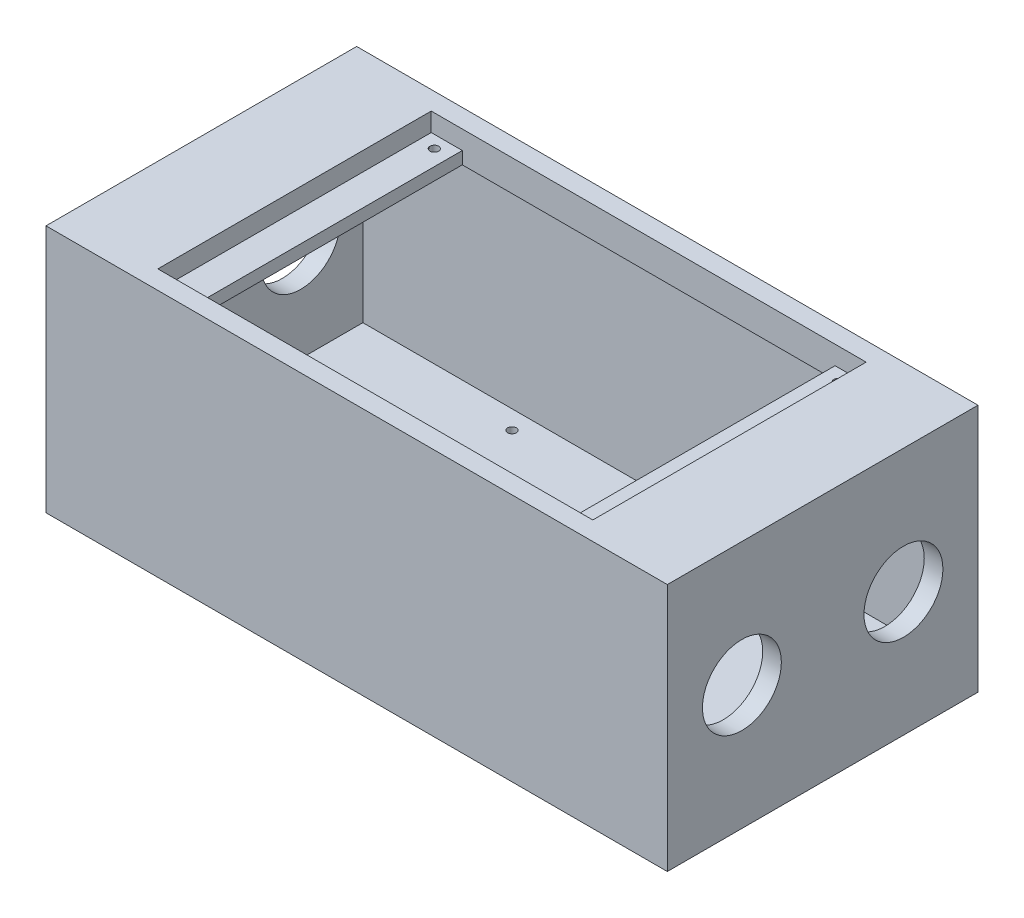
SolidWorks part; units mm, degrees
other "Markup1"
sketch "Sketch8" plane through (250, -50, -125) normal (1, 0, 0) x (0, 0, -1)
ref_plane "Front Plane" through (0, 0, 0) normal (0, 0, 1) x (1, 0, 0)
ref_plane "Top Plane" through (0, 0, 0) normal (0, 1, 0) x (1, 0, 0)
ref_plane "Right Plane" through (0, 0, 0) normal (1, 0, 0) x (0, 0, -1)
sketch "Sketch1" plane through (0, 0, 0) normal (1, 0, 0) x (0, 0, -1)
  line L1 (-125, -100) -> (125, -100)
  line L2 (-125, -100) -> (-125, 100)
  line L3 (-125, 100) -> (125, 100)
  line L4 (125, -100) -> (125, 100)
  line L5 (-125, -100) -> (125, 100) construction
  line L6 (-125, 100) -> (125, -100) construction
  point P0 (0, 0)
  dimension "D1" = 250
  dimension "D2" = 200
extrude "Boss-Extrude1" add sketch "Sketch1" along normal mid plane 500
sketch "Sketch7" plane through (0, 0, 0) normal (0, 1, 0) x (1, 0, 0)
  line L1 (-235, -115) -> (235, -115)
  line L2 (-235, -115) -> (-235, 115)
  line L3 (-235, 115) -> (235, 115)
  line L4 (235, -115) -> (235, 115)
  line L5 (-235, -115) -> (235, 115) construction
  line L6 (-235, 115) -> (235, -115) construction
  point P0 (0, 0)
  dimension "D1" = 470
  dimension "D2" = 230
extrude "Cut-Extrude4" cut sketch "Sketch7" against normal mid plane 160
sketch "Sketch5" plane through (250, 0, 0) normal (1, 0, 0) x (0, 0, -1)
  line L0 (-125, 100) -> (-125, -100) construction
  circle A0 centre (-65, 0) radius 31.75
  dimension "D1" = 63.5
  dimension "D2" = 60
extrude "63.5mm_dia_servo" cut sketch "Sketch5" against normal blind 20
mirror "Mirror12" about plane through (0, 0, 0) normal (0, 0, 1) of "63.5mm_dia_servo"
mirror "Mirror13" about plane through (0, 0, 0) normal (1, 0, 0) of "Mirror12", "63.5mm_dia_servo"
sketch "Sketch10" plane through (0, 100, 0) normal (0, 1, 0) x (1, 0, 0)
  line L1 (-175, -110) -> (175, -110)
  line L2 (-175, -110) -> (-175, 110)
  line L3 (-175, 110) -> (175, 110)
  line L4 (175, -110) -> (175, 110)
  line L5 (-175, -110) -> (175, 110) construction
  line L6 (-175, 110) -> (175, -110) construction
  point P0 (0, 0)
  dimension "D1" = 350
  dimension "D2" = 220
extrude "Cut-Extrude5" cut sketch "Sketch10" against normal blind 20
ref_plane "Plane4" through (0, 75, 0) normal (0, 1, 0) x (1, 0, 0)
sketch "Sketch15" plane through (0, 75, 0) normal (0, 1, 0) x (1, 0, 0)
  line L1 (-250, -125) -> (250, -125)
  line L2 (-250, -125) -> (-250, 125)
  line L3 (-250, 125) -> (250, 125)
  line L4 (250, -125) -> (250, 125)
  line L5 (-250, -125) -> (250, 125) construction
  line L6 (-250, 125) -> (250, -125) construction
  point P0 (0, 0)
extrude "Boss-Extrude2" add sketch "Sketch15" along normal blind 10
sketch "Sketch18" plane through (0, 85, 0) normal (0, 1, 0) x (1, 0, 0)
  line L0 (175, 110) -> (-175, 110) construction
  line L1 (-150, -110) -> (150, -110)
  line L2 (-150, -110) -> (-150, 110)
  line L3 (-150, 110) -> (150, 110)
  line L4 (150, -110) -> (150, 110)
  line L5 (-150, -110) -> (150, 110) construction
  line L6 (-150, 110) -> (150, -110) construction
  point P0 (0, 0)
  dimension "D1" = 300
extrude "Cut-Extrude11" cut sketch "Sketch18" against normal blind 10
sketch "Sketch19" plane through (0, 85, 0) normal (0, 1, 0) x (1, 0, 0)
  line L0 (175, 110) -> (-175, 110) construction
  circle A0 centre (-162.5, 100) radius 3.5
  dimension "D2" = 7
  dimension "D1" = 162.5
  dimension "D3" = 10
extrude "Cut-Extrude12" cut sketch "Sketch19" against normal blind 10
mirror "Mirror14" about plane through (0, 0, 0) normal (0, 0, 1) of "Cut-Extrude12"
mirror "Mirror15" about plane through (0, 0, 0) normal (1, 0, 0) of "Mirror14", "Cut-Extrude12"
sketch "Sketch20" plane through (0, -80, 0) normal (0, 1, 0) x (1, 0, 0)
  line L0 (175, 110) -> (-175, 110) construction
  circle A0 centre (-100, 100) radius 3.5
  dimension "D1" = 7
  dimension "D2" = 100
  dimension "D3" = 10
extrude "Cut-Extrude13" cut sketch "Sketch20" against normal blind 10
mirror "Mirror16" about plane through (0, 0, 0) normal (0, 0, 1) of "Cut-Extrude13"
mirror "Mirror17" about plane through (0, 0, 0) normal (1, 0, 0) of "Mirror16", "Cut-Extrude13"
